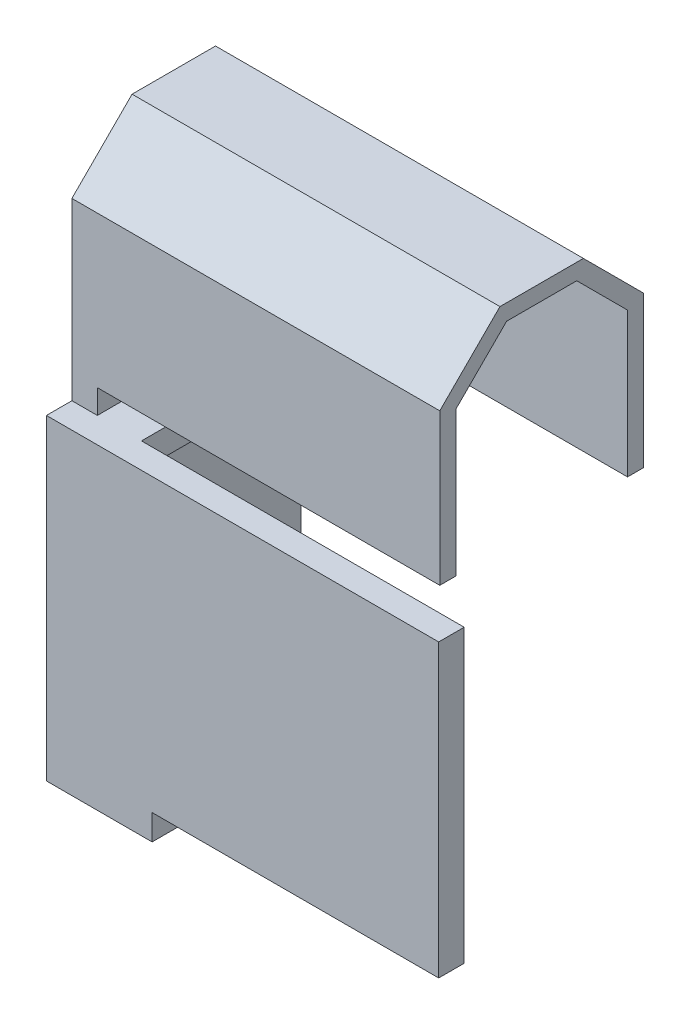
SolidWorks part; units mm, degrees
material "PLA"
ref_plane "Front Plane" through (0, 0, 0) normal (0, 0, 1) x (1, 0, 0)
ref_plane "Top Plane" through (0, 0, 0) normal (0, 1, 0) x (1, 0, 0)
ref_plane "Right Plane" through (0, 0, 0) normal (1, 0, 0) x (0, 0, -1)
sketch "Sketch1" plane through (0, 0, 0) normal (1, 0, 0) x (0, 0, -1)
  line L0 (-12.7, 0) -> (-12.7, -13.6385)
  line L1 (12.7, 0) -> (12.7, -13.6385)
  line L2 (12.7, -13.6385) -> (-12.7, -13.6385)
  line L3 (0, 12.7) -> (-22.6112, 12.7) construction
  line L4 (-12.7, 0) -> (-12.7, 12.7)
  line L5 (-12.7, 12.7) -> (12.7, 12.7)
  line L6 (12.7, 12.7) -> (12.7, 0)
  circle A0 centre (0, 0) radius 3
  dimension "D1" = 6
extrude "Boss-Extrude1" add sketch "Sketch1" along normal blind 3.175
sketch "Sketch2" plane through (0, 0, 0) normal (-1, 0, 0) x (0, 0, 1)
  line L3 (-10.7, -11.6385) -> (-10.7, -13.6385)
  line L4 (-12.7, -13.6385) -> (12.7, -13.6385) construction
  line L5 (10.7, -11.6385) -> (10.7, -13.6385)
  line L6 (-10.7, 10.7) -> (-10.7, -11.6385)
  line L7 (-10.7, -11.6385) -> (10.7, -11.6385)
  line L8 (10.7, -11.6385) -> (10.7, 10.7)
  line L9 (-10.7, 10.7) -> (-10.7, -11.6385)
  line L11 (10.7, -11.6385) -> (10.7, 10.7)
  line L12 (10.7, -13.6385) -> (12.7, -13.6385)
  line L15 (-12.7, 12.7) -> (-12.7, -13.6385)
  line L16 (-12.7, -13.6385) -> (12.7, -13.6385)
  line L17 (12.7, -13.6385) -> (12.7, 12.7)
  line L18 (-12.7, 12.7) -> (-12.7, -13.6385)
  line L19 (-12.7, -13.6385) -> (-10.7, -13.6385)
  line L20 (12.7, -13.6385) -> (12.7, 12.7)
  line L23 (10.7, 10.7) -> (-10.7, 10.7)
  line L24 (10.7, 10.7) -> (-10.7, 10.7)
  line L25 (12.7, 12.7) -> (-12.7, 12.7)
  line L26 (12.7, 12.7) -> (-12.7, 12.7)
  dimension "D1" = 2
  dimension "D2" = 0
extrude "Boss-Extrude2" add sketch "Sketch2" along normal blind 8.5
sketch "Sketch3" plane through (-8.5, 0, 0) normal (-1, 0, 0) x (0, 0, 1)
  line L0 (-10.7, -13.6385) -> (10.7, -13.6385)
  line L6 (-12.7, 12.7) -> (-12.7, -13.6385)
  line L7 (-12.7, -13.6385) -> (-10.7, -13.6385)
  line L8 (-10.7, -13.6385) -> (-10.7, 10.7)
  line L9 (10.7, 10.7) -> (10.7, -13.6385)
  line L10 (10.7, -13.6385) -> (12.7, -13.6385)
  line L11 (12.7, -13.6385) -> (12.7, 12.7)
  line L12 (-12.7, 12.7) -> (-12.7, -13.6385)
  line L13 (-12.7, -13.6385) -> (-10.7, -13.6385)
  line L16 (10.7, -13.6385) -> (12.7, -13.6385)
  line L17 (12.7, -13.6385) -> (12.7, 12.7)
  line L21 (12.7, 12.7) -> (-12.7, 12.7)
  line L22 (12.7, 12.7) -> (-12.7, 12.7)
  line L23 (-10.7, 10.7) -> (10.7, 10.7)
  circle A0 centre (0, 0) radius 7
  dimension "D2" = 14
  dimension "D1" = 0
extrude "Boss-Extrude3" add sketch "Sketch3" along normal blind 3.175
sketch "Sketch4" plane through (0, -13.6385, 0) normal (0, -1, 0) x (1, 0, 0)
  line L0 (3.175, 12.7) -> (-11.675, 12.7) construction
  line L1 (-11.675, -12.7) -> (-8.503, -12.7)
  line L2 (-11.675, -12.7) -> (-11.675, 12.7)
  line L3 (-11.675, 12.7) -> (-8.503, 12.7)
  line L4 (-8.503, -12.7) -> (-8.503, 12.7)
extrude "Boss-Extrude4" add sketch "Sketch4" along normal blind 42.45
sketch "Sketch5" plane through (3.175, 0, 0) normal (1, 0, 0) x (0, 0, -1)
  circle A0 centre (0, 0) radius 3
  circle A1 centre (0, 0) radius 5
  dimension "D1" = 10
extrude "Boss-Extrude5" add sketch "Sketch5" along normal blind 5
chamfer "Chamfer2" distance 7.5 angle 45 4 edges at (-4.25, 12.7, 12.7) (-4.25, 12.7, -12.7) (-4.25, 10.7, 10.7) (-4.25, 10.7, -10.7)
sketch "Sketch7" plane through (-8.503, 0, 0) normal (1, 0, 0) x (0, 0, -1)
  line L0 (-12.7, -56.0885) -> (-12.7, -13.6385) construction
  line L4 (-12.7, -19.8135) -> (-12.7, -16.6385)
  line L5 (9.2423, -18.3135) -> (9.25, -19.9135) construction
  line L6 (12.7, -56.0885) -> (12.7, -13.6385) construction
  line L10 (12.7, -19.8135) -> (12.7, -16.6385)
  line L13 (-12.7, -16.6385) -> (12.7, -16.6385)
  line L14 (-12.7, -19.8135) -> (12.7, -19.8135)
  line L15 (12.7, -13.6385) -> (-12.7, -13.6385) construction
  dimension "D1" = 3.175
  dimension "D2" = 3.175
  dimension "D3" = 3
extrude "Boss-Extrude6" add sketch "Sketch7" along normal blind 5.5
sketch "Sketch9" plane through (-8.503, 0, 0) normal (1, 0, 0) x (0, 0, -1)
  line L0 (12.7, -56.0885) -> (12.7, -19.8135) construction
  line L1 (-12.7, -56.0885) -> (12.7, -56.0885)
  line L2 (-12.7, -56.0885) -> (-12.7, -52.9135)
  line L3 (-12.7, -52.9135) -> (12.7, -52.9135)
  line L4 (12.7, -56.0885) -> (12.7, -52.9135)
  dimension "D1" = 3.175
extrude "Boss-Extrude7" add sketch "Sketch9" along normal blind 10
sketch "Sketch10" plane through (3.175, 0, 0) normal (1, 0, 0) x (0, 0, -1)
  line L6 (5.2, 12.7) -> (-5.2, 12.7)
  line L7 (-5.2, 12.7) -> (-12.7, 5.2)
  line L8 (-12.7, 5.2) -> (-12.7, -13.6385)
  line L9 (-12.7, -13.6385) -> (12.7, -13.6385)
  line L10 (12.7, -13.6385) -> (12.7, 5.2)
  line L11 (12.7, 5.2) -> (5.2, 12.7)
  line L12 (5.2, 12.7) -> (-5.2, 12.7)
  line L13 (-5.2, 12.7) -> (-12.7, 5.2)
  line L14 (-12.7, 5.2) -> (-12.7, -13.6385)
  line L16 (12.7, -13.6385) -> (12.7, 5.2)
  line L17 (12.7, 5.2) -> (5.2, 12.7)
  line L18 (-10.7, -11.6385) -> (-10.7, -13.6385)
  line L19 (-10.7, -13.6385) -> (-12.7, -13.6385)
  line L20 (10.7, -11.6385) -> (10.7, -13.6385)
  line L21 (10.7, -13.6385) -> (12.7, -13.6385)
  line L24 (4.3716, 10.7) -> (-4.3716, 10.7)
  line L25 (-4.3716, 10.7) -> (-10.7, 4.3716)
  line L26 (-10.7, 4.3716) -> (-10.7, -11.6385)
  line L27 (-10.7, -11.6385) -> (10.7, -11.6385)
  line L28 (10.7, -11.6385) -> (10.7, 4.3716)
  line L29 (10.7, 4.3716) -> (4.3716, 10.7)
  line L30 (4.3716, 10.7) -> (-4.3716, 10.7)
  line L31 (-4.3716, 10.7) -> (-10.7, 4.3716)
  line L32 (-10.7, 4.3716) -> (-10.7, -11.6385)
  line L34 (10.7, -11.6385) -> (10.7, 4.3716)
  line L35 (10.7, 4.3716) -> (4.3716, 10.7)
  dimension "D1" = 0
  dimension "D2" = 2
extrude "Boss-Extrude8" add sketch "Sketch10" along normal blind 31
sketch "Sketch12" plane through (0, 0, 12.7) normal (0, 0, 1) x (1, 0, 0)
  line L0 (-3.003, -16.6385) -> (-11.675, -16.6385) construction
  line L1 (-11.675, -56.0885) -> (-11.675, 5.2) construction
  line L2 (-11.675, -52.9135) -> (-11.675, -56.0885)
  line L3 (-11.675, -16.6385) -> (37.215, -16.6385)
  line L4 (-11.675, -16.6385) -> (-11.675, -52.9135)
  line L5 (1.497, -52.9135) -> (37.215, -52.9135)
  line L6 (37.215, -16.6385) -> (37.215, -52.9135)
  line L7 (-11.675, -56.0885) -> (1.497, -56.0885)
  line L8 (1.497, -56.0885) -> (-11.675, -56.0885) construction
  line L9 (1.497, -56.0885) -> (1.497, -52.9135)
  dimension "D1" = 48.89
extrude "Boss-Extrude11" add sketch "Sketch12" along normal blind 3.175
